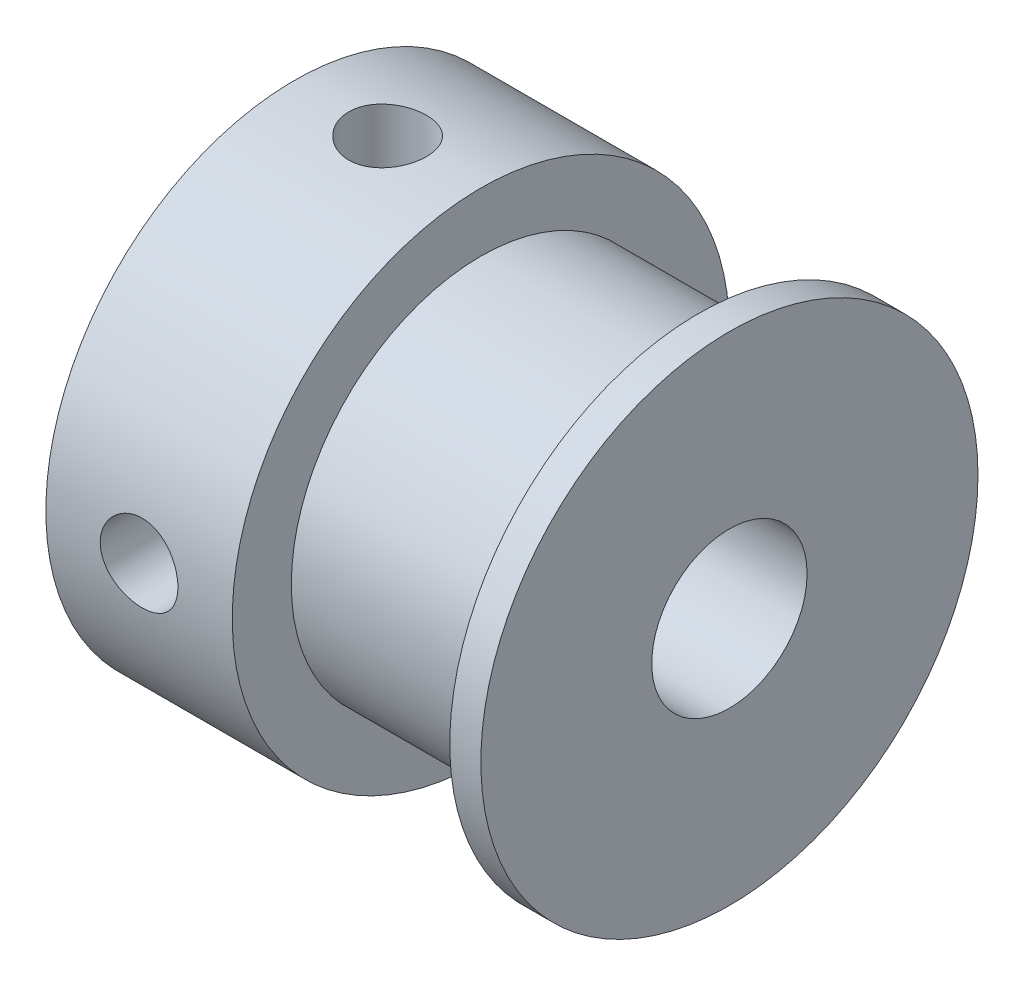
SolidWorks part; units mm, degrees
material "6061-T6 (SS)"
ref_plane "Front Plane" through (0, 0, 0) normal (0, 0, 1) x (1, 0, 0)
ref_plane "Top Plane" through (0, 0, 0) normal (0, 1, 0) x (1, 0, 0)
ref_plane "Right Plane" through (0, 0, 0) normal (1, 0, 0) x (0, 0, -1)
sketch "Sketch1" plane through (0, 0, 0) normal (0, 0, 1) x (1, 0, 0)
  line L0 (0, 2.5) -> (0, 8)
  line L1 (0, 8) -> (6, 8)
  line L2 (6, 8) -> (6, 6.1)
  line L3 (6, 6.1) -> (13, 6.1)
  line L4 (13, 6.1) -> (13, 8)
  line L5 (13, 8) -> (14, 8)
  line L6 (14, 8) -> (14, 2.5)
  line L7 (14, 2.5) -> (0, 2.5)
  line L8 (0, 0) -> (-7.6744, 0) construction
  dimension "D1" = 5
  dimension "D2" = 16
  dimension "D3" = 12.2
  dimension "D4" = 6
  dimension "D5" = 14
  dimension "D6" = 1
revolve "Revolve1" add sketch "Sketch1" angle 360 about L8
hole_wizard "M3x0.5 Tapped Hole1" positions "Sketch3" profile "Sketch2" tap size "M3x0.5" standard "ANSI Metric"
sketch "Sketch3" plane through (0, 0, 0) normal (0, 1, 0) x (1, 0, 0)
  line L0 (0, 0) -> (6, 0) construction
  line L1 (6, -6.1) -> (6, 6.1) construction
  point P8 (3, 0)
sketch "Sketch2" plane through (3, 0, 0) normal (1, 0, 0) x (0, 0, -1)
  line L0 (0, 0) -> (0, 8)
  line L1 (0, 8) -> (1.25, 8)
  line L2 (1.25, 8) -> (1.25, 0)
  line L5 (1.25, 0) -> (0, 0)
  line L11 (0, -6.35) -> (0, 107.95) construction
  dimension "Thread Major Dia." = 2.5
  dimension "Thru Tap Drill Depth" = 8
hole_wizard "M3x0.5 Tapped Hole2" positions "Sketch5" profile "Sketch4" tap size "M3x0.5" standard "ANSI Metric"
sketch "Sketch5" plane through (0, 0, 0) normal (0, 0, 1) x (1, 0, 0)
  line L0 (0, 0) -> (6, 0) construction
  line L1 (6, -6.1) -> (6, 6.1) construction
  point P7 (3, 0)
sketch "Sketch4" plane through (3, 0, 0) normal (1, 0, 0) x (0, 1, 0)
  line L0 (0, 0) -> (0, 8)
  line L1 (0, 8) -> (1.25, 8)
  line L2 (1.25, 8) -> (1.25, 0)
  line L5 (1.25, 0) -> (0, 0)
  line L11 (0, -6.35) -> (0, 107.95) construction
  dimension "Thread Major Dia." = 2.5
  dimension "Thru Tap Drill Depth" = 8
